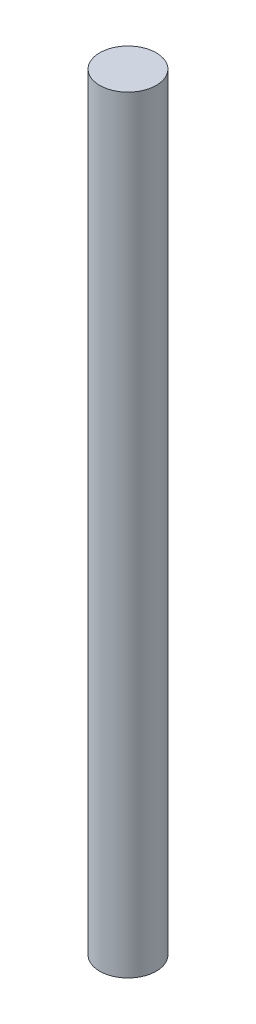
SolidWorks part; units mm, degrees
ref_plane "Front Plane" through (0, 0, 0) normal (0, 0, 1) x (1, 0, 0)
ref_plane "Top Plane" through (0, 0, 0) normal (0, 1, 0) x (1, 0, 0)
ref_plane "Right Plane" through (0, 0, 0) normal (1, 0, 0) x (0, 0, -1)
sketch "Sketch1" plane through (0, 0, 0) normal (0, 1, 0) x (1, 0, 0)
  circle A0 centre (0, 0) radius 1.4
  dimension "D1" = 2.8
extrude "Boss-Extrude1" add sketch "Sketch1" along normal blind 38
